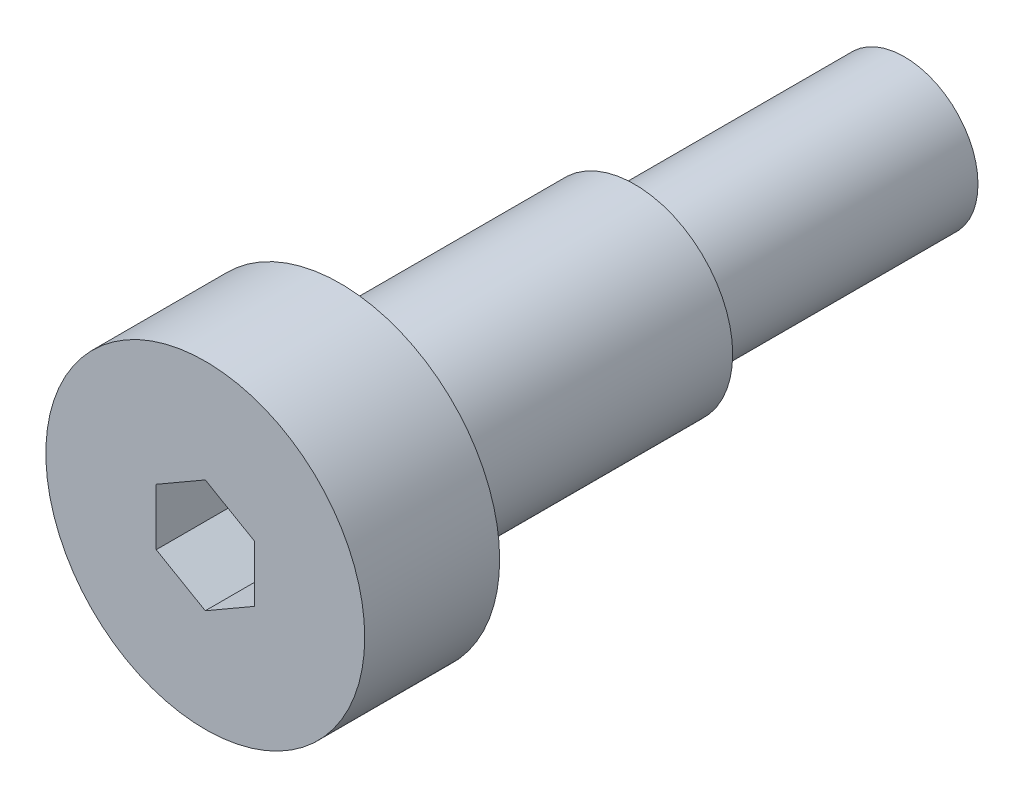
SolidWorks part; units mm, degrees
ref_plane "前视基准面" through (0, 0, 0) normal (0, 0, 1) x (1, 0, 0)
ref_plane "上视基准面" through (0, 0, 0) normal (0, 1, 0) x (1, 0, 0)
ref_plane "右视基准面" through (0, 0, 0) normal (1, 0, 0) x (0, 0, -1)
other "Configuration Table"
sketch "Profile_1" plane through (0, 0, 0) normal (0, 0, 1) x (1, 0, 0)
  circle A0 centre (0, 0) radius 4
extrude "Shoulder" add sketch "Profile_1" along normal blind 12 from offset 7
sketch "Profile_2" plane through (0, 0, 0) normal (0, 0, 1) x (1, 0, 0)
  circle A0 centre (0, 0) radius 3
extrude "M6_thread" add sketch "Profile_2" along normal blind 11 from offset 4
sketch "Profile_3" plane through (0, 0, 0) normal (0, 0, 1) x (1, 0, 0)
  line L0 (2, 1.1547) -> (0, 2.3094)
  line L1 (0, 2.3094) -> (-2, 1.1547)
  line L2 (-2, 1.1547) -> (-2, -1.1547)
  line L3 (-2, -1.1547) -> (0, -2.3094)
  line L4 (0, -2.3094) -> (2, -1.1547)
  line L5 (2, -1.1547) -> (2, 1.1547)
  circle A0 centre (0, 0) radius 6.5
extrude "Socket_head" add sketch "Profile_3" along normal blind 5.5 from offset 19
